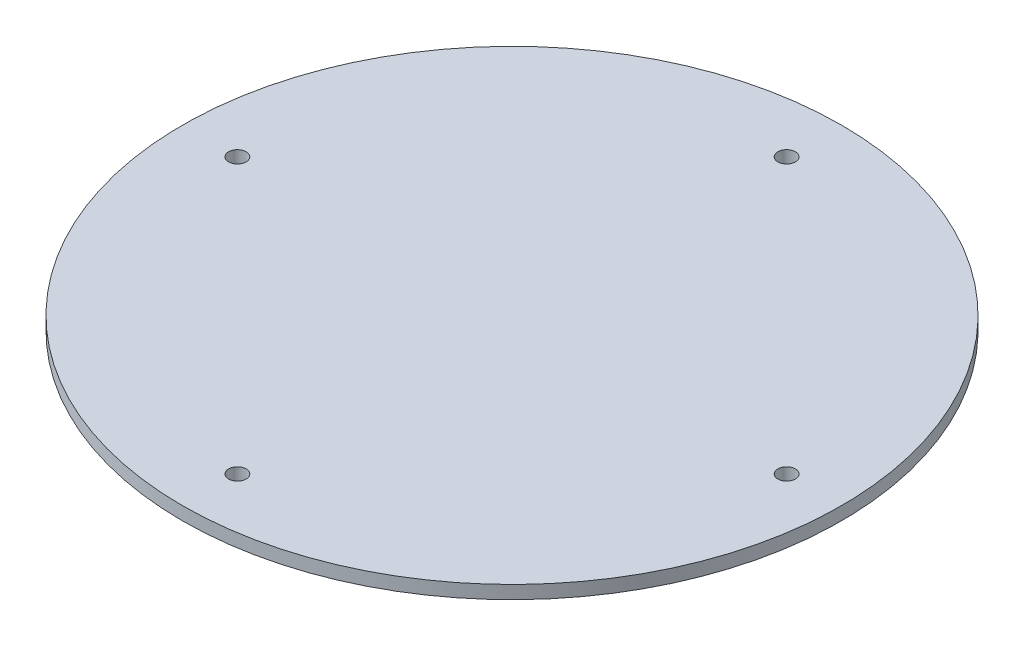
SolidWorks part; units mm, degrees
material "1060 Alloy"
ref_plane "Front Plane" through (0, 0, 0) normal (0, 0, 1) x (1, 0, 0)
ref_plane "Top Plane" through (0, 0, 0) normal (0, 1, 0) x (1, 0, 0)
ref_plane "Right Plane" through (0, 0, 0) normal (1, 0, 0) x (0, 0, -1)
sketch "Sketch1" plane through (0, 0, 0) normal (0, 1, 0) x (1, 0, 0)
  line L0 (0, 0) -> (0, 62.5) construction
  circle A1 centre (0, 0) radius 75
  circle A2 centre (0, 62.5) radius 2
  circle A3 centre (62.5, 0) radius 2
  circle A4 centre (0, -62.5) radius 2
  circle A5 centre (-62.5, 0) radius 2
  point P14 (0, 0)
  dimension "D1" = 150
  dimension "D2" = 4
  dimension "D3" = 62.5
  dimension "D4" = 4
extrude "Boss-Extrude1" add sketch "Sketch1" along normal blind 3
sketch "Sketch2" plane through (0, 3, 0) normal (0, 1, 0) x (1, 0, 0)
  line L1 (-53.033, 53.033) -> (53.033, 53.033)
  line L2 (-53.033, 53.033) -> (-53.033, -53.033)
  line L3 (-53.033, -53.033) -> (53.033, -53.033)
  line L4 (53.033, 53.033) -> (53.033, -53.033)
  circle A0 centre (0, 0) radius 75 construction
